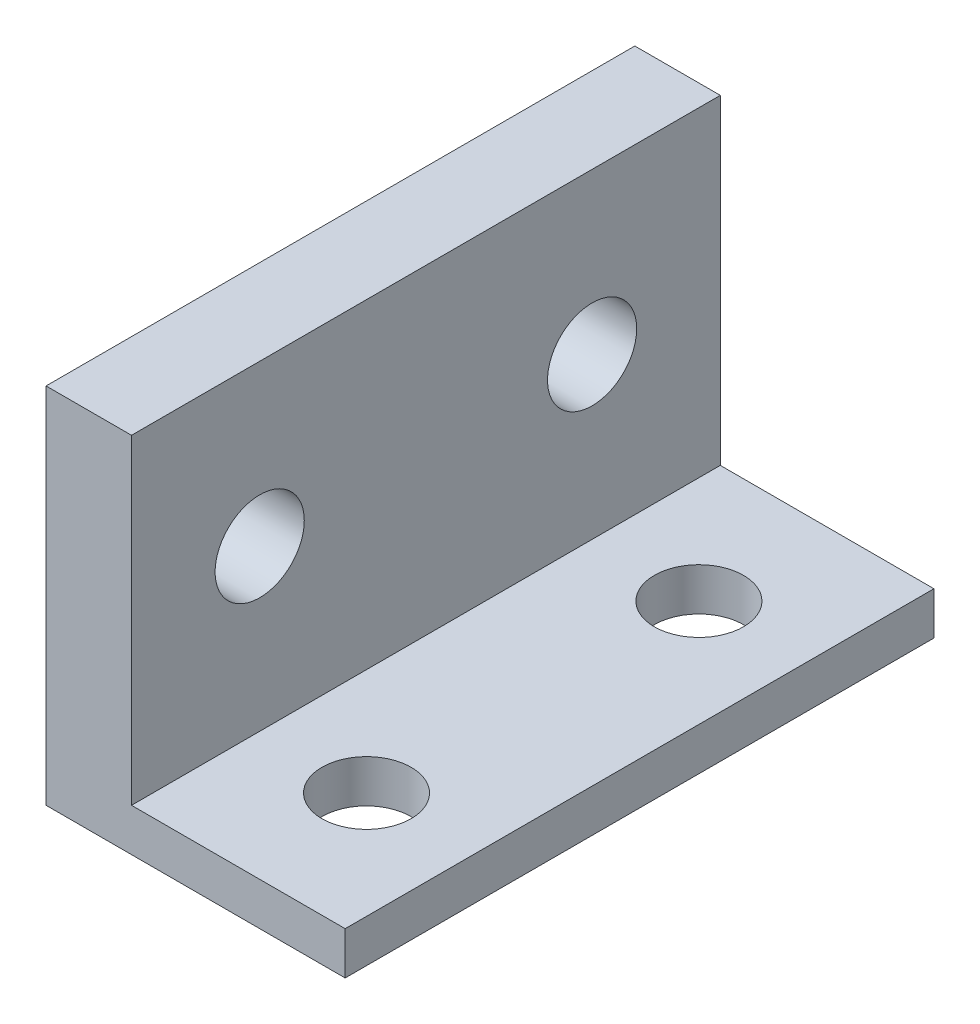
SolidWorks part; units mm, degrees
ref_plane "Front Plane" through (0, 0, 0) normal (0, 0, 1) x (1, 0, 0)
ref_plane "Top Plane" through (0, 0, 0) normal (0, 1, 0) x (1, 0, 0)
ref_plane "Right Plane" through (0, 0, 0) normal (1, 0, 0) x (0, 0, -1)
sketch "Sketch1" plane through (0, 0, 0) normal (0, 0, 1) x (1, 0, 0)
  line L1 (0, 0) -> (17.78, 0)
  line L2 (0, 0) -> (0, 2.54)
  line L3 (0, 2.54) -> (17.78, 2.54)
  line L4 (17.78, 0) -> (17.78, 2.54)
  line L5 (0, 2.54) -> (5.08, 2.54)
  line L6 (0, 2.54) -> (0, 21.59)
  line L7 (0, 21.59) -> (5.08, 21.59)
  line L8 (5.08, 2.54) -> (5.08, 21.59)
  dimension "D1" = 5.08
  dimension "D2" = 12.7
  dimension "D3" = 19.05
  dimension "D4" = 2.54
extrude "Boss-Extrude1" add sketch "Sketch1" along normal blind 35 contours L6 L5 L8 L7 | L2 L1 L4 L3
hole_wizard "Ø5.0mm Dowel Hole1" positions "Sketch2" profile "Sketch3" hole size "Ø5.0" standard "ANSI Metric" end condition through all
sketch "Sketch2" plane through (5.08, 0, 0) normal (1, 0, 0) x (0, 0, -1)
  line L0 (-35, 12.065) -> (0, 12.065) construction
  line L1 (-35, 2.54) -> (-35, 21.59) construction
  line L2 (0, 2.54) -> (0, 21.59) construction
  point P0 (-27.38, 12.065)
  point P2 (-7.62, 12.065)
  point P12 (0, 0)
  point P13 (0, 0)
  dimension "D1" = 7.62
  dimension "D2" = 7.62
sketch "Sketch3" plane through (5.08, 12.065, 27.38) normal (0, 1, 0) x (0, 0, -1)
  line L0 (0, 0) -> (0, 5.08)
  line L1 (0, 5.08) -> (2.65, 5.08)
  line L2 (2.65, 5.08) -> (2.65, 0)
  line L5 (2.65, 0) -> (0, 0)
  line L11 (0, -6.35) -> (0, 107.95) construction
  dimension "Thru Hole Dia." = 5.3
  dimension "Thru Hole Depth" = 5.08
hole_wizard "Ø5.0mm Dowel Hole2" positions "Sketch4" profile "Sketch5" hole size "Ø5.0" standard "ANSI Metric" end condition through all
sketch "Sketch4" plane through (0, 2.54, 0) normal (0, 1, 0) x (1, 0, 0)
  line L0 (5.08, 0) -> (17.78, 0) construction
  line L1 (5.08, -35) -> (17.78, -35) construction
  line L2 (11.43, 0) -> (11.43, -35) construction
  point P0 (11.43, -27.38)
  point P2 (11.43, -7.62)
  point P13 (0, 0)
  point P14 (8.89, -7.62)
  dimension "D1" = 7.62
  dimension "D2" = 7.62
sketch "Sketch5" plane through (11.43, 2.54, 27.38) normal (1, 0, 0) x (0, 0, 1)
  line L0 (0, 0) -> (0, 2.54)
  line L1 (0, 2.54) -> (2.65, 2.54)
  line L2 (2.65, 2.54) -> (2.65, 0)
  line L5 (2.65, 0) -> (0, 0)
  line L11 (0, -6.35) -> (0, 107.95) construction
  dimension "Thru Hole Dia." = 5.3
  dimension "Thru Hole Depth" = 2.54
equation "\"wall thicc\"= 2.5mm"
equation "\"press fit\"= 0.3mm"
equation "\"shaft thick\"= 5mm + \"press fit\""
equation "\"D1@Sketch1\"=\"wall thicc\"*2"
equation "\"D4@Sketch1\"=\"wall thicc\""
